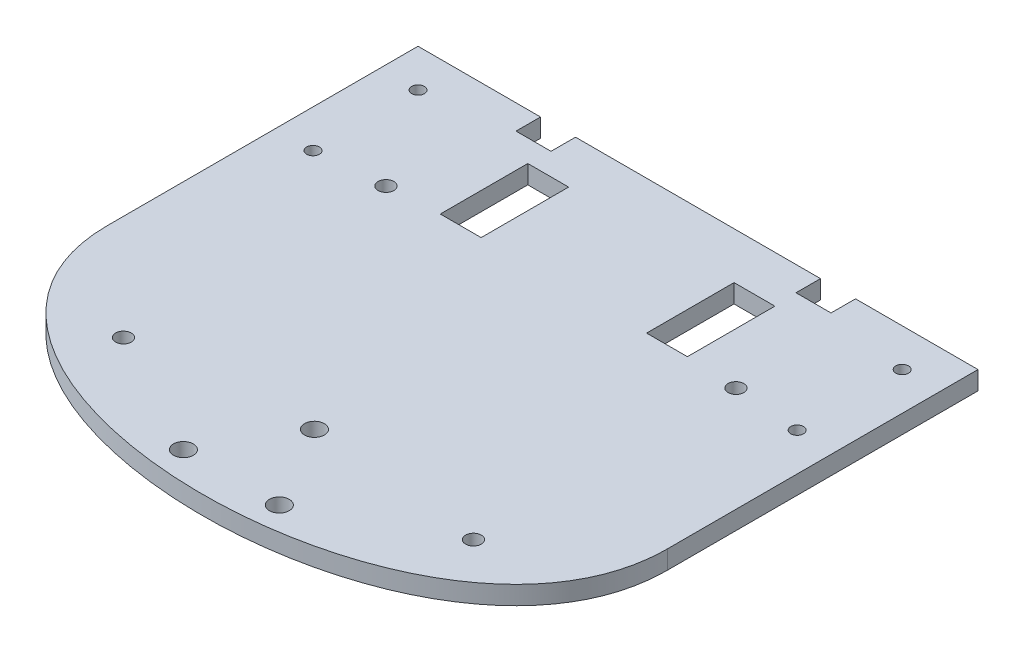
SolidWorks part; units mm, degrees
ref_plane "Front Plane" through (0, 0, 0) normal (0, 0, 1) x (1, 0, 0)
ref_plane "Top Plane" through (0, 0, 0) normal (0, 1, 0) x (1, 0, 0)
ref_plane "Right Plane" through (0, 0, 0) normal (1, 0, 0) x (0, 0, -1)
sketch "Sketch2" plane through (0, 0, 0) normal (0, 1, 0) x (1, 0, 0)
  line L4 (-48, -33.6908) -> (-48, 91.0268) construction
  line L5 (48, -42.5) -> (-48, -42.5) construction
  line L6 (48, -42.5) -> (48, 42.5) construction
  line L7 (48, 42.5) -> (-48, 42.5)
  line L8 (-48, -42.5) -> (-48, 42.5) construction
  line L9 (48, -42.5) -> (-48, 42.5) construction
  line L10 (48, 42.5) -> (-48, -42.5) construction
  line L11 (48, 148.5724) -> (48, -105.4276) construction
  line L12 (-48, 42.5) -> (-48, -10.75)
  line L13 (48, 42.5) -> (48, -10.75)
  spline S0 degree 3 poles (-48, -10.75) (-48, -53.0833) (48, -53.0833) (48, -10.75) knots 0 0 0 0 1 1 1 1
  point P0 (0, 0)
  dimension "D3" = 180
  dimension "D4" = 127
  dimension "D5" = 85
  dimension "D1" = 96
  dimension "D2" = 180
  dimension "D6" = 127
extrude "Boss-Extrude1" add sketch "Sketch2" along normal blind 3.175
sketch "Sketch3" plane through (0, 3.175, 0) normal (0, 1, 0) x (1, 0, 0)
  line L0 (0, 0) -> (0, 15) construction
  line L10 (48, 42.5) -> (-48, 42.5) construction
  line L11 (-41.5, 36) -> (-41.5, 18) construction
  line L12 (41.5, 36) -> (41.5, 18) construction
  line L13 (-30, 19) -> (-30, -26) construction
  line L14 (30, 19) -> (30, -26) construction
  line L15 (0, -42.5) -> (28.6945, -42.5) construction
  line L16 (-21.18, 34.5) -> (-14.18, 34.5)
  line L17 (-21.18, 34.5) -> (-21.18, 19.5)
  line L18 (-21.18, 19.5) -> (-14.18, 19.5)
  line L19 (-14.18, 34.5) -> (-14.18, 19.5)
  line L20 (-48, 42.5) -> (-48, -10.75) construction
  line L24 (14.18, 34.5) -> (21.18, 34.5)
  line L25 (14.18, 34.5) -> (14.18, 19.5)
  line L26 (14.18, 19.5) -> (21.18, 19.5)
  line L27 (21.18, 34.5) -> (21.18, 19.5)
  circle A0 centre (-41.5, 36) radius 1.0922
  circle A1 centre (-41.5, 18) radius 1.0922
  circle A2 centre (-30, 19) radius 1.35
  circle A3 centre (41.5, 18) radius 1.0922
  circle A4 centre (41.5, 36) radius 1.0922
  circle A5 centre (-30, -26) radius 1.35
  circle A6 centre (30, -26) radius 1.35
  circle A7 centre (30, 19) radius 1.35
  circle A8 centre (-8.225, -37.5) radius 1.7
  circle A9 centre (8.225, -37.5) radius 1.7
  circle A10 centre (0, -23.2539) radius 1.7
  spline S1 degree 3 poles (-48, -10.75) (-48, -53.0833) (48, -53.0833) (48, -10.75) knots 0 0 0 0 1 1 1 1 construction
  point P12 (0, -27.2597)
  dimension "D5" = 2.1844
  dimension "D6" = 2.1844
  dimension "D9" = 2.7
  dimension "D13" = 3.4
  dimension "D2" = 6.5
  dimension "D3" = 1.5
  dimension "D4" = 7
  dimension "D7" = 18
  dimension "D8" = 16.45
  dimension "D10" = 23.5
  dimension "D11" = 30
  dimension "D12" = 45
  dimension "D14" = 20.32
  dimension "D15" = 15
  dimension "D16" = 16.45
  dimension "D17" = 16.45
  dimension "D18" = 8
  dimension "D19" = 5
extrude "Cut-Extrude1" cut sketch "Sketch3" against normal through all and the other way through all
sketch "Sketch5" plane through (0, 3.175, 0) normal (0, 1, 0) x (1, 0, 0)
  line L0 (0, -0.2815) -> (0, 85.2815) construction
  line L10 (21, 42.5) -> (27, 42.5)
  line L11 (21, 42.5) -> (21, 38.3)
  line L12 (21, 38.3) -> (27, 38.3)
  line L13 (27, 42.5) -> (27, 38.3)
  line L18 (-27, 42.5) -> (-21, 42.5)
  line L19 (-27, 42.5) -> (-27, 38.3)
  line L20 (-27, 38.3) -> (-21, 38.3)
  line L21 (-21, 42.5) -> (-21, 38.3)
  point P2 (-24, 38.3)
  dimension "D1" = 6
  dimension "D2" = 4.2
  dimension "D3" = 6
  dimension "D4" = 4.2
extrude "Cut-Extrude2" cut sketch "Sketch5" against normal through all
